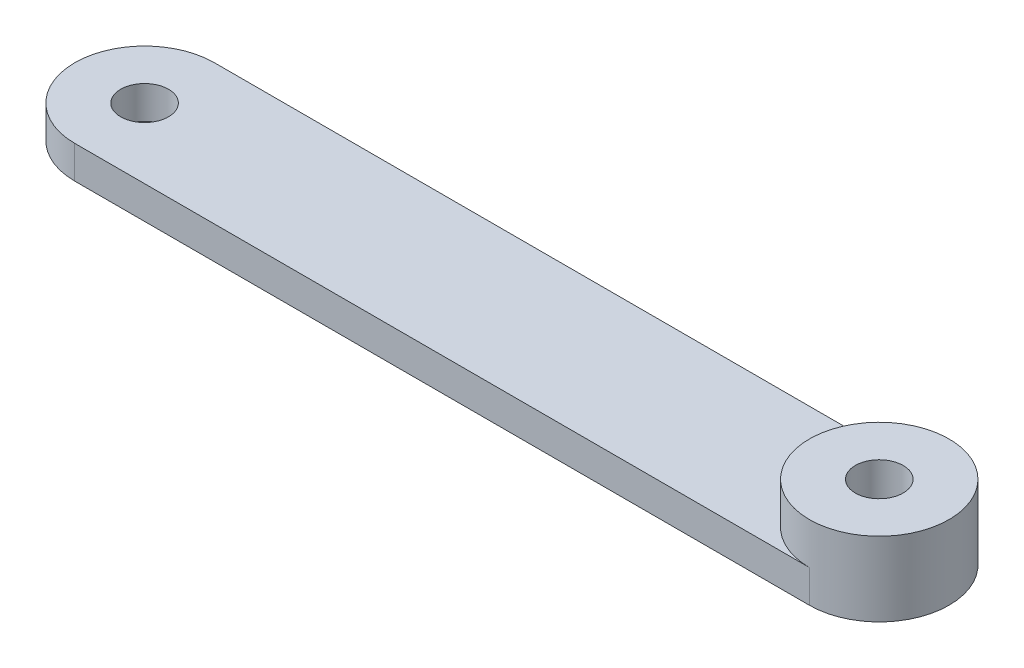
SolidWorks part; units mm, degrees
material "PET"
ref_plane "Front" through (0, 0, 0) normal (0, 0, 1) x (1, 0, 0)
ref_plane "Top" through (0, 0, 0) normal (0, 1, 0) x (1, 0, 0)
ref_plane "Right" through (0, 0, 0) normal (1, 0, 0) x (0, 0, -1)
sketch "Sketch1" plane through (0, 0, 0) normal (0, 1, 0) x (1, 0, 0)
  line L1 (-23.1719, 5.6259) -> (43.6281, 5.6259)
  line L3 (-23.1719, -7.0741) -> (43.6281, -7.0741)
  line L5 (-23.1719, 5.6259) -> (43.6281, -7.0741) construction
  line L6 (-23.1719, -7.0741) -> (43.6281, 5.6259) construction
  arc A0 (-23.1719, 5.6259) -> (-23.1719, -7.0741) centre (-23.1719, -0.7241) ccw
  arc A1 (43.6281, 5.6259) -> (43.6281, -7.0741) centre (43.6281, -0.7241) cw
  point P4 (10.2281, -0.7241)
  dimension "D1" = 6.35
  dimension "D3" = 12.7
extrude "Boss-Extrude1" add sketch "Sketch1" along normal blind 2.975
sketch "Sketch2" plane through (0, 2.975, 0) normal (0, 1, 0) x (1, 0, 0)
  circle A0 centre (-23.1719, -0.7241) radius 2.175
  circle A2 centre (43.6281, -0.7241) radius 2.175
  dimension "D1" = 4.35
  dimension "D2" = 66.8
  dimension "D3" = 4.35
extrude "Cut-Extrude1" cut sketch "Sketch2" against normal blind 12.7
sketch "Sketch3" plane through (0, 2.975, 0) normal (0, 1, 0) x (1, 0, 0)
  circle A0 centre (43.6281, -0.7241) radius 2.175
  arc A2 (43.6281, 5.6259) -> (43.6281, -7.0741) centre (43.6281, -0.7241) cw
  arc A3 (43.6281, 5.6259) -> (43.6281, -7.0741) centre (43.6281, -0.7241) ccw
extrude "Boss-Extrude2" add sketch "Sketch3" along normal blind 3.775
